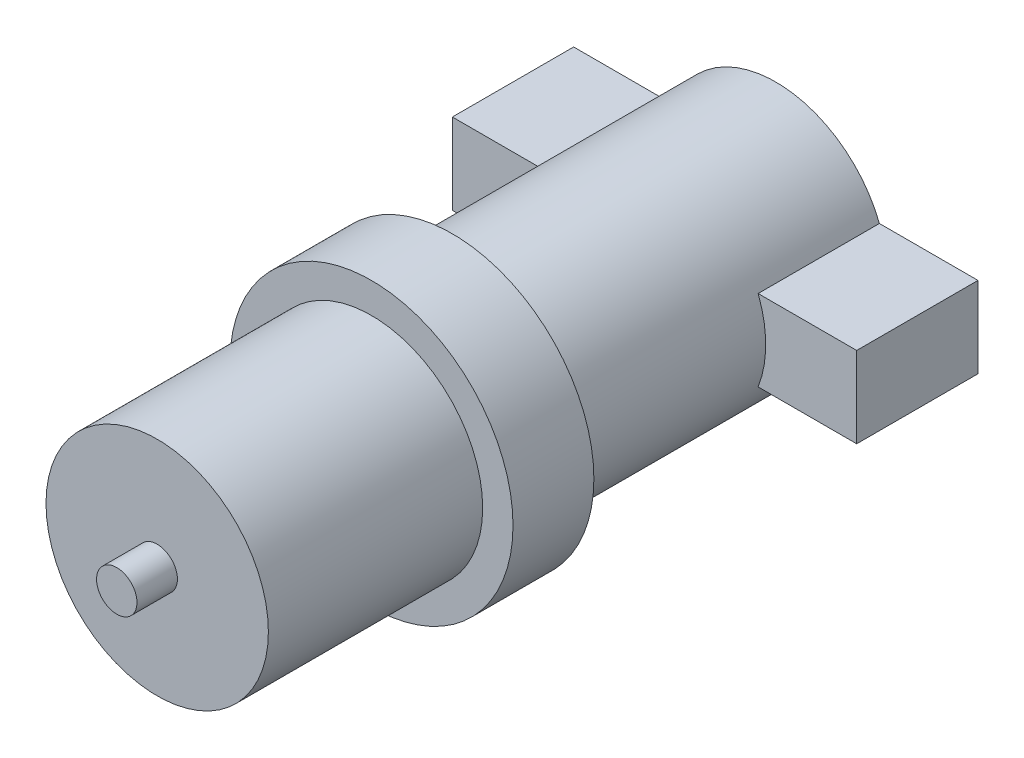
SolidWorks part; units mm, degrees
ref_plane "Front Plane" through (0, 0, 0) normal (0, 0, 1) x (1, 0, 0)
ref_plane "Top Plane" through (0, 0, 0) normal (0, 1, 0) x (1, 0, 0)
ref_plane "Right Plane" through (0, 0, 0) normal (1, 0, 0) x (0, 0, -1)
sketch "Sketch1" plane through (0, 0, 0) normal (0, 0, 1) x (1, 0, 0)
  circle A0 centre (0, 0) radius 6.875
  dimension "D1" = 13.75
extrude "Boss-Extrude1" add sketch "Sketch1" along normal blind 7.5
sketch "Sketch2" plane through (0, 0, 7.5) normal (0, 0, 1) x (1, 0, 0)
  circle A0 centre (0, 0) radius 8.75
  dimension "D1" = 17.5
extrude "Boss-Extrude2" add sketch "Sketch2" along normal blind 5
sketch "Sketch3" plane through (0, 0, 12.5) normal (0, 0, 1) x (1, 0, 0)
  circle A0 centre (0, 0) radius 6.875
  circle A1 centre (0, 0) radius 6.875 construction
extrude "Boss-Extrude3" add sketch "Sketch3" along normal blind 13.25
sketch "Sketch4" plane through (0, 0, 25.75) normal (0, 0, 1) x (1, 0, 0)
  circle A0 centre (0, 0) radius 1.25
  dimension "D1" = 2.5
extrude "Boss-Extrude4" add sketch "Sketch4" along normal blind 2.5
sketch "Sketch5" plane through (0, 0, 0) normal (0, 0, -1) x (-1, 0, 0)
  circle A0 centre (0, 0) radius 6.875
  circle A1 centre (0, 0) radius 6.875 construction
extrude "Boss-Extrude5" add sketch "Sketch5" along normal blind 12.5
sketch "Sketch8" plane through (0, 0, -12.5) normal (0, 0, -1) x (-1, 0, 0)
  line L1 (-12.5, -2.5) -> (12.5, -2.5)
  line L2 (-12.5, -2.5) -> (-12.5, 2.5)
  line L3 (-12.5, 2.5) -> (12.5, 2.5)
  line L4 (12.5, -2.5) -> (12.5, 2.5)
  line L5 (-12.5, -2.5) -> (12.5, 2.5) construction
  line L6 (-12.5, 2.5) -> (12.5, -2.5) construction
  point P0 (0, 0)
  dimension "D1" = 5
  dimension "D2" = 25
extrude "Boss-Extrude6" add sketch "Sketch8" against normal blind 7.5
